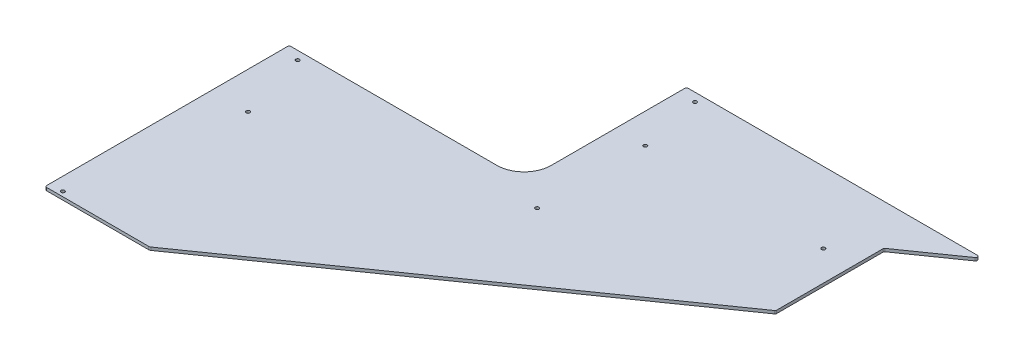
SolidWorks part; units mm, degrees
material "PC High Viscosity"
ref_plane "Front Plane" through (0, 0, 0) normal (0, 0, 1) x (1, 0, 0)
ref_plane "Top Plane" through (0, 0, 0) normal (0, 1, 0) x (1, 0, 0)
ref_plane "Right Plane" through (0, 0, 0) normal (1, 0, 0) x (0, 0, -1)
sketch "Sketch1"
  line L0 (0, 0) -> (0, 469.9)
  line L1 (0, 469.9) -> (439.7375, 469.9)
  line L2 (439.7375, 469.9) -> (439.7375, 773.938)
  line L3 (439.7375, 773.938) -> (994.2054, 773.938)
  line L4 (885.3805, 697.738) -> (885.3805, 495.4532)
  line L5 (885.3805, 495.4532) -> (177.8, 0)
  line L6 (177.8, 0) -> (0, 0)
  line L7 (69.0753, 323.85) -> (792.9753, 323.85) construction
  line L8 (495.8715, 438.15) -> (495.8715, 640.588) construction
  line L9 (495.8715, 640.588) -> (829.2465, 640.588) construction
  line L11 (994.2054, 773.938) -> (885.3805, 697.738)
  circle A0 centre (24.6253, 21.463) radius 3.3782
  circle A1 centre (69.0753, 323.85) radius 3.3782
  circle A2 centre (495.8715, 438.15) radius 3.3782
  circle A3 centre (495.8715, 640.588) radius 3.3782
  circle A4 centre (829.2465, 640.588) radius 3.3782
other "AlignGroup1" parameters "D1"=3.9696, "D2"=116.6316, "D3"=20.3469, "D4"=15.577, "D5"=60.058, "D6"=371.9449, "D7"=256.553, "D8"=307.8153, "D9"=50.8, "D10"=399.54, "D11"=66.7682, "D12"=433.4399, "D13"=369.0921, "D14"=108.994, "D15"=278.8449, "D16"=307.975, "D17"=438.15, "D18"=640.588, "D19"=134.2709, "D20"=134.2709
other "AlignGroup2"
extrude "Boss-Extrude1" add sketch "Sketch1" along normal blind 5.588
fillet "Fillet1" radius 50.8 1 edges at (439.7375, 2.794, -469.9)
sketch "Sketch2" plane through (0, 5.588, 0) normal (0, 1, 0) x (1, 0, 0)
  line L0 (0, 454.025) -> (31.75, 454.025) construction
  line L1 (0, 469.9) -> (0, 0) construction
  line L2 (31.75, 454.025) -> (31.75, 469.9) construction
  line L3 (388.9375, 469.9) -> (0, 469.9) construction
  line L4 (439.7375, 758.063) -> (471.4875, 758.063) construction
  line L5 (439.7375, 773.938) -> (439.7375, 520.7) construction
  line L6 (471.4875, 758.063) -> (471.4875, 773.938) construction
  line L7 (994.2054, 773.938) -> (439.7375, 773.938) construction
  line L8 (716.9714, 773.938) -> (716.9714, 377.5319) construction
  line L9 (177.8, 0) -> (885.3805, 495.4532) construction
  circle A0 centre (31.75, 454.025) radius 3.3782
  circle A1 centre (471.4875, 758.063) radius 3.3782
  dimension "D4" = 6.7564
  dimension "D1" = 15.875
  dimension "D2" = 31.75
  dimension "D3" = 31.75
extrude "Cut-Extrude1" cut sketch "Sketch2" against normal through all
fillet "Fillet2" radius 3.175 7 edges at (0, 2.794, -469.9) (439.7375, 2.794, -773.938) (885.3805, 2.794, -495.4532) (177.8, 2.794, 0) (0, 2.794, 0) (994.2054, 2.794, -773.938) (885.3805, 2.794, -697.738)
sketch "Sketch3" plane through (0, 5.588, 0) normal (0, 1, 0) x (1, 0, 0)
  line L0 (178.62, 0.5742) -> (884.0266, 494.5052) construction
  line L2 (3.175, 0) -> (176.7989, 0) construction
  line L3 (3.175, 0) -> (176.7989, 0)
  line L4 (3.175, 12.7) -> (193.9353, 12.7)
  line L5 (178.62, 0.5742) -> (197.5775, 13.8484)
  line L6 (0, 466.725) -> (0, 3.175) construction
  line L7 (0, 15.875) -> (0, 3.175)
  arc A0 (0, 3.175) -> (3.175, 0) centre (3.175, 3.175) ccw construction
  arc A1 (0, 3.175) -> (3.175, 0) centre (3.175, 3.175) ccw
  arc A2 (0, 15.875) -> (3.175, 12.7) centre (3.175, 15.875) ccw
  arc A3 (193.9353, 12.7) -> (197.5775, 13.8484) centre (193.9353, 19.05) ccw
  arc A4 (176.7989, 0) -> (178.62, 0.5742) centre (176.7989, 3.175) ccw construction
  arc A5 (176.7989, 0) -> (178.62, 0.5742) centre (176.7989, 3.175) ccw
  point P13 (193.4502, 12.7)
  point P15 (196.5207, 13.1084)
  dimension "D3" = 6.35
  dimension "D2" = 12.7
  dimension "D1" = 2
extrude "Cut-Extrude2" cut sketch "Sketch3" against normal through all
